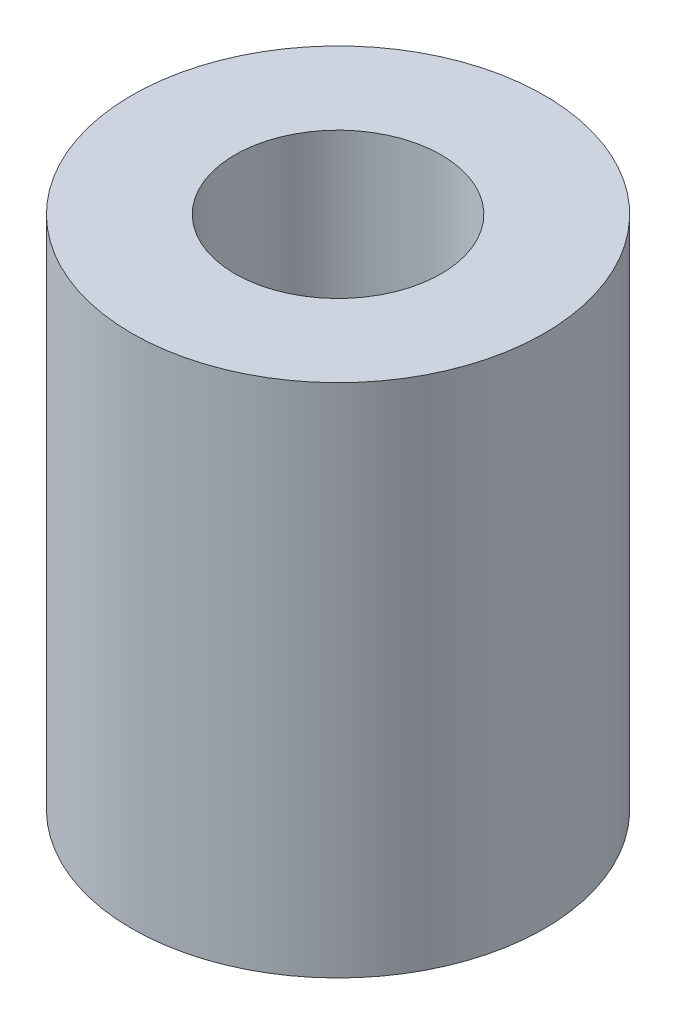
SolidWorks part; units mm, degrees
material "6061-T6 (SS)"
ref_plane "Front Plane" through (0, 0, 0) normal (0, 0, 1) x (1, 0, 0)
ref_plane "Top Plane" through (0, 0, 0) normal (0, 1, 0) x (1, 0, 0)
ref_plane "Right Plane" through (0, 0, 0) normal (1, 0, 0) x (0, 0, -1)
sketch "Sketch1" plane through (0, 0, 0) normal (0, 1, 0) x (1, 0, 0)
  circle A1 centre (0, 0) radius 10
  dimension "D1" = 20
extrude "Boss-Extrude1" add sketch "Sketch1" along normal blind 25
sketch "Sketch2" plane through (0, 25, 0) normal (0, 1, 0) x (1, 0, 0)
  circle A0 centre (0, 0) radius 3.175
  dimension "D1" = 6.35
extrude "Cut-Extrude1" cut sketch "Sketch2" against normal through all
sketch "Sketch3" plane through (0, 25, 0) normal (0, 1, 0) x (1, 0, 0)
  circle A0 centre (0, 0) radius 5
  dimension "D1" = 10
extrude "Cut-Extrude2" cut sketch "Sketch3" against normal blind 12.5
